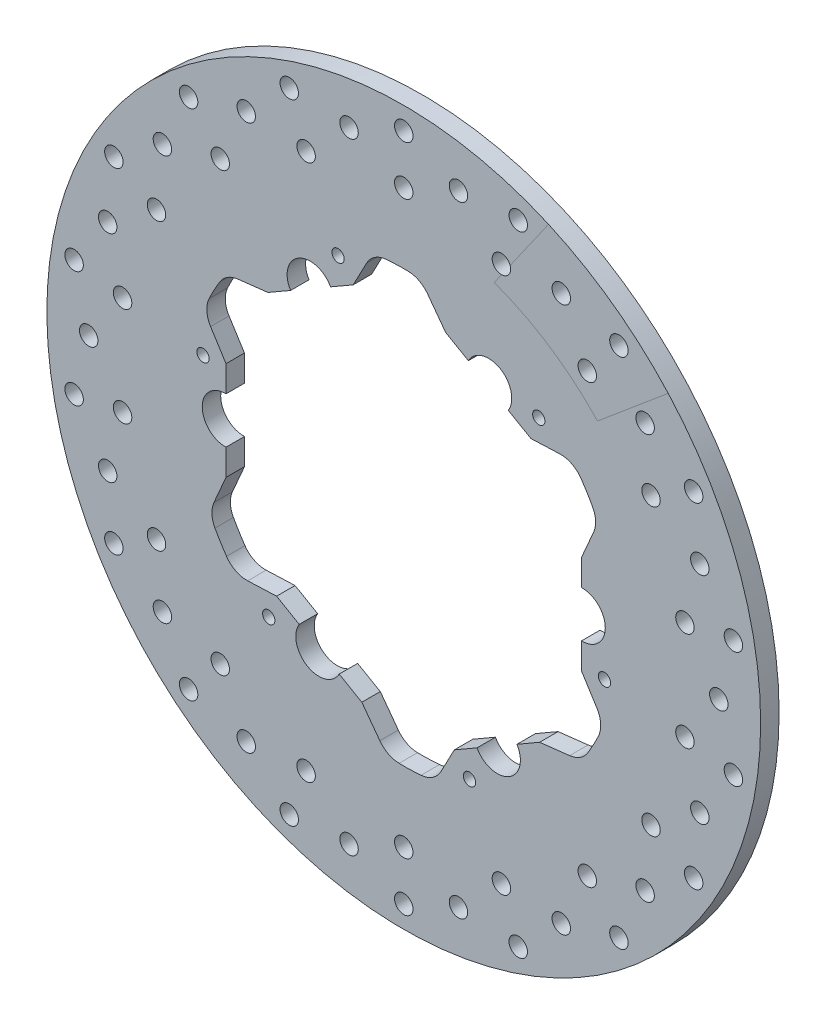
SolidWorks part; units mm, degrees
material "Gray Cast Iron"
ref_plane "Front Plane" through (0, 0, 0) normal (0, 0, 1) x (1, 0, 0)
ref_plane "Top Plane" through (0, 0, 0) normal (0, 1, 0) x (1, 0, 0)
ref_plane "Right Plane" through (0, 0, 0) normal (1, 0, 0) x (0, 0, -1)
sketch "Sketch1" plane through (0, 0, 0) normal (0, 0, 1) x (1, 0, 0)
  line L0 (-55.5625, 0) -> (-55.5625, -25.0191) construction
  line L1 (-45.8597, 11.4094) -> (-45.8597, 4.6599)
  line L2 (-45.8597, 11.4094) -> (-51.6236, 20.5474)
  line L3 (-45.8597, -13.9906) -> (-50.1583, -23.9026)
  line L4 (-45.8597, -7.2411) -> (-45.8597, -13.9906)
  line L5 (-13.049, 45.4204) -> (-8.0172, 54.981)
  line L6 (-13.049, 45.4204) -> (-18.8943, 42.0456)
  line L7 (-29.2008, 36.0951) -> (-35.0461, 32.7204)
  line L8 (-35.0461, 32.7204) -> (-45.7794, 31.4871)
  line L9 (32.8107, 34.011) -> (43.6064, 34.4336)
  line L10 (32.8107, 34.011) -> (26.9654, 37.3857)
  line L11 (16.6589, 43.3362) -> (10.8136, 46.711)
  line L12 (10.8136, 46.711) -> (4.3789, 55.3897)
  line L13 (45.8597, -11.4094) -> (51.6236, -20.5474)
  line L14 (45.8597, -11.4094) -> (45.8597, -4.6599)
  line L15 (45.8597, 7.2411) -> (45.8597, 13.9906)
  line L16 (45.8597, 13.9906) -> (50.1583, 23.9026)
  line L17 (13.049, -45.4204) -> (8.0172, -54.981)
  line L18 (13.049, -45.4204) -> (18.8943, -42.0456)
  line L19 (29.2008, -36.0951) -> (35.0461, -32.7204)
  line L20 (35.0461, -32.7204) -> (45.7794, -31.4871)
  line L21 (-32.8107, -34.011) -> (-43.6064, -34.4336)
  line L22 (-32.8107, -34.011) -> (-26.9654, -37.3857)
  line L23 (-16.6589, -43.3362) -> (-10.8136, -46.711)
  line L24 (-10.8136, -46.711) -> (-4.3789, -55.3897)
  circle A0 centre (0, 0) radius 92.075
  arc A1 (-45.7794, 31.4871) -> (-51.6236, 20.5474) centre (0, 0) ccw
  arc A3 (-45.8597, 4.6599) -> (-45.8597, -7.2411) centre (-46.0375, -1.2906) ccw
  arc A4 (-18.8943, 42.0456) -> (-29.2008, 36.0951) centre (-24.1364, 39.2243) ccw
  arc A5 (26.9654, 37.3857) -> (16.6589, 43.3362) centre (21.9011, 40.5149) ccw
  arc A6 (45.8597, -4.6599) -> (45.8597, 7.2411) centre (46.0375, 1.2906) ccw
  arc A7 (18.8943, -42.0456) -> (29.2008, -36.0951) centre (24.1364, -39.2243) ccw
  arc A8 (-26.9654, -37.3857) -> (-16.6589, -43.3362) centre (-21.9011, -40.5149) ccw
  arc A9 (4.3789, 55.3897) -> (-8.0172, 54.981) centre (0, 0) ccw
  arc A10 (50.1583, 23.9026) -> (43.6064, 34.4336) centre (0, 0) ccw
  arc A11 (45.7794, -31.4871) -> (51.6236, -20.5474) centre (0, 0) ccw
  arc A12 (-4.3789, -55.3897) -> (8.0172, -54.981) centre (0, 0) ccw
  arc A13 (-55.5625, 0) -> (-43.6064, -34.4336) centre (0, 0) ccw
  point P50 (0, 0)
  dimension "D1" = 184.15
  dimension "D2" = 111.125
  dimension "D3" = 11.9062
  dimension "D4" = 9.525
  dimension "D5" = 0.1778
  dimension "D6" = 25.4
  dimension "D7" = 44.45
  dimension "D9" = 47.2577
  dimension "D8" = 6
extrude "Boss-Extrude1" add sketch "Sketch1" along normal blind 4.7625
fillet "Fillet1" radius 6.35 12 edges at (8.0172, -54.981, 2.3813) (45.7794, -31.4871, 2.3813) (-4.3789, -55.3897, 2.3813) (-43.6064, -34.4336, 2.3813) (51.6236, -20.5474, 2.3813) (50.1583, 23.9026, 2.3813) (43.6064, 34.4336, 2.3813) (4.3789, 55.3897, 2.3813) (-50.1583, -23.9026, 2.3813) (-51.6236, 20.5474, 2.3813) (-8.0172, 54.981, 2.3813) (-45.7794, 31.4871, 2.3813)
sketch "Sketch4" plane through (0, 0, 4.7625) normal (0, 0, 1) x (1, 0, 0)
  circle A0 centre (-16.953, 50.0113) radius 1.5875
  arc A1 (-18.8943, 42.0456) -> (-29.2008, 36.0951) centre (-24.1364, 39.2243) ccw construction
  circle A3 centre (34.8346, 39.6874) radius 1.5875
  circle A4 centre (51.7876, -10.3239) radius 1.5875
  circle A5 centre (16.953, -50.0113) radius 1.5875
  circle A6 centre (-34.8346, -39.6874) radius 1.5875
  circle A7 centre (-51.7876, 10.3239) radius 1.5875
  point P6 (-27.113, 44.3799)
  point P23 (0, 0)
  dimension "D1" = 52.8066
  dimension "D2" = 3.175
  dimension "D3" = 10.16
  dimension "D4" = 6
extrude "Cut-Extrude1" cut sketch "Sketch4" against normal through all
sketch "Sketch5" plane through (0, 0, 4.7625) normal (0, 0, 1) x (1, 0, 0)
  line L0 (0, 120.6115) -> (0, 84.6416) construction
  line L1 (-74.0774, 0) -> (83.9652, 0) construction
  line L2 (0, 0) -> (20.7529, 117.6956) construction
  circle A0 centre (0, 0) radius 68.58 construction
  circle A4 centre (0, 86.36) radius 2.3812
  circle A5 centre (0, 73.66) radius 2.3812
  circle A6 centre (14.1141, 80.0452) radius 2.3812
  dimension "D1" = 137.16
  dimension "D2" = 4.7625
  dimension "D3" = 12.7
  dimension "D4" = 86.36
  dimension "D5" = 10
  dimension "D6" = 81.28
extrude "Cut-Extrude2" cut sketch "Sketch5" against normal through all
sketch "Sketch6" plane through (0, 0, 4.7625) normal (0, 0, 1) x (1, 0, 0)
  line L0 (0, 0) -> (0, 110.5188) construction
  line L1 (0, 0) -> (38.9978, 107.1456) construction
  line L4 (23.3472, 64.1458) -> (37.3582, 84.1556)
  line L5 (49.9701, 46.5054) -> (68.2294, 61.8268)
  arc A2 (68.2294, 61.8268) -> (37.3582, 84.1556) centre (0, 0) ccw
  arc A3 (49.9701, 46.5054) -> (23.3472, 64.1458) centre (0, 0) ccw
  dimension "D2" = 15
  dimension "D3" = 184.15
  dimension "D6" = 136.525
  dimension "D1" = 20
  dimension "D4" = 15
  dimension "D5" = 38.1
split line "Split Line1"
pattern_circular "FrontPaternCopy" count 18 over 360 about axis through (0, 0, 0) along (0, 0, 1) of "Cut-Extrude2"
sketch "Sketch7" plane through (0, 0, 4.7625) normal (0, 0, 1) x (1, 0, 0)
  line L0 (0, 0) -> (-24.1364, 39.2243) construction
equation "\"holenumber\"=18"
equation "\"D1@FrontPaternCopy\"=\"holenumber\""
